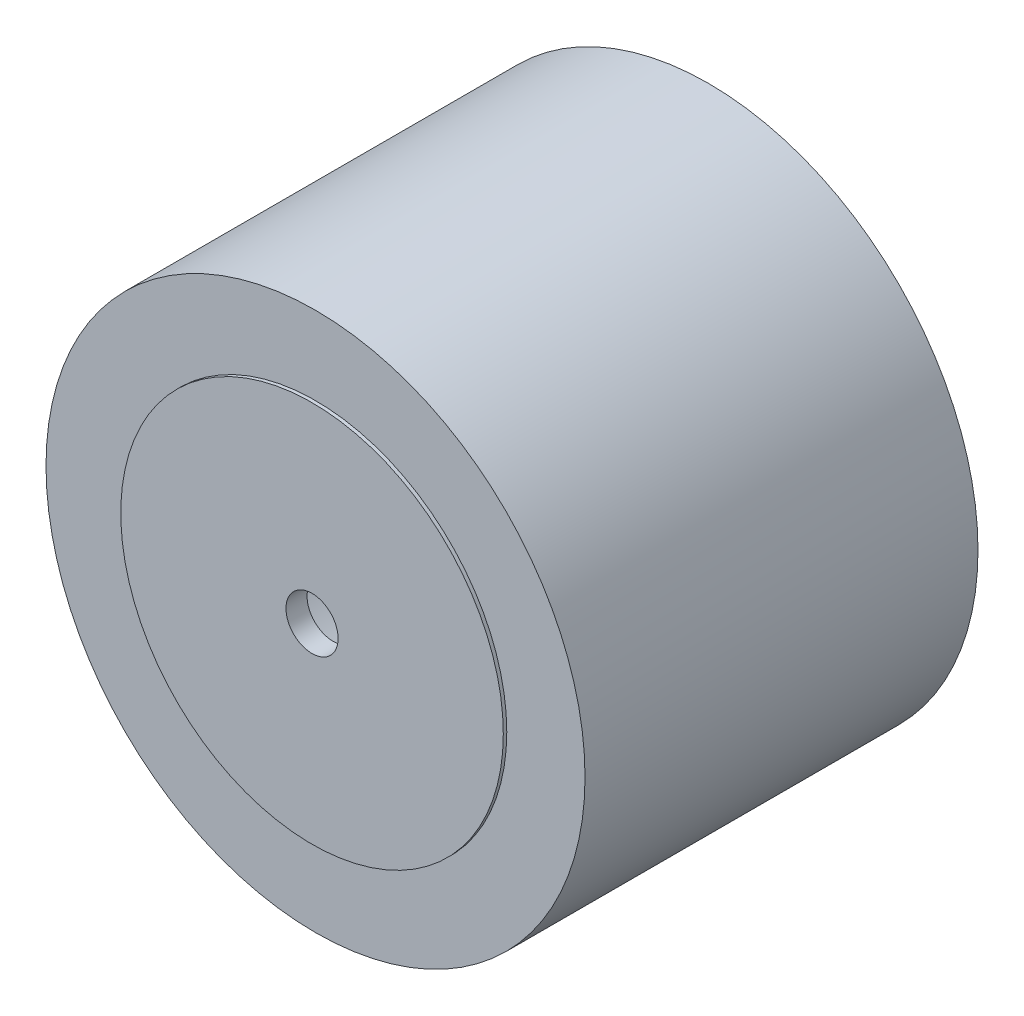
SolidWorks part; units mm, degrees
ref_plane "Alzado" through (0, 0, 0) normal (0, 0, 1) x (1, 0, 0)
ref_plane "Planta" through (0, 0, 0) normal (0, 1, 0) x (1, 0, 0)
ref_plane "Vista lateral" through (0, 0, 0) normal (1, 0, 0) x (0, 0, -1)
sketch "Croquis1" plane through (0, 0, 0) normal (0, 1, 0) x (1, 0, 0)
  line L0 (0, 0) -> (0, 7.5811) construction
  line L2 (1.5, 1.0135) -> (8.5, 1.0135)
  line L3 (8.5, 1.0135) -> (8.5, 22.8)
  line L4 (8.5, 22.8) -> (11, 22.8)
  line L5 (11, 22.8) -> (11, 22.6)
  line L6 (11, 22.6) -> (15.5, 22.6)
  line L7 (15.5, 22.6) -> (15.5, 0)
  line L9 (15.5, 0) -> (11, 0)
  line L10 (11, 0) -> (11, -0.2)
  line L11 (11, -0.2) -> (1.5, -0.2)
  line L13 (1.5, 1.0135) -> (1.5, -0.2)
  dimension "D1" = 1.5
  dimension "D2" = 8.5
  dimension "D3" = 15.5
  dimension "D4" = 11
  dimension "D5" = 23
  dimension "D6" = 0.2
  dimension "D7" = 0.2
  dimension "D8" = 11
revolve "Revolución1" add sketch "Croquis1" angle 360 about L0
